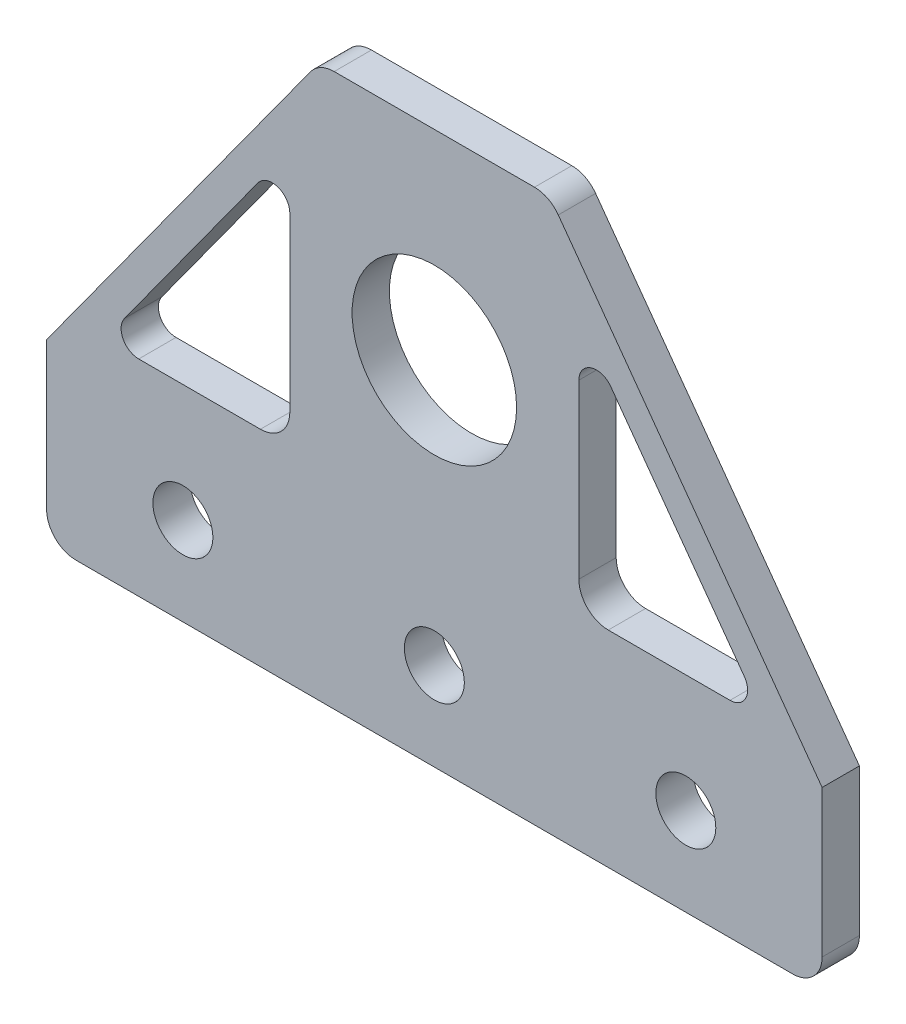
SolidWorks part; units mm, degrees
material "6061-T6 (SS)"
ref_plane "Front Plane" through (0, 0, 0) normal (0, 0, 1) x (1, 0, 0)
ref_plane "Top Plane" through (0, 0, 0) normal (0, 1, 0) x (1, 0, 0)
ref_plane "Right Plane" through (0, 0, 0) normal (1, 0, 0) x (0, 0, -1)
sketch "Sketch1" plane through (0, 0, 0) normal (0, 0, 1) x (1, 0, 0)
  line L0 (9.8, 25) -> (9.8, 52)
  line L1 (-9.8, 25) -> (-9.8, 52)
  line L2 (-9.8, 47) -> (9.8, 47) construction
  line L3 (9.8, 52) -> (-9.8, 52)
  line L4 (9.8, 25) -> (9.8, 10)
  line L5 (-9.8, 25) -> (-9.8, 10)
  line L6 (0, 10) -> (0, 25) construction
  line L12 (9.8, 25) -> (-9.8, 25)
  line L13 (9.8, 10) -> (-9.8, 10)
  line L20 (9.8, 52) -> (9.8, 57)
  line L21 (9.8, 57) -> (-9.8, 57)
  line L22 (-9.8, 57) -> (-9.8, 52)
  circle A2 centre (0, 17.5) radius 2.5527
  circle A3 centre (0, 40) radius 7
  point P15 (0, 47)
  dimension "D3" = 5
  dimension "D4" = 5
  dimension "D5" = 19.6
  dimension "D6" = 15
  dimension "D2" = 15
extrude "Boss-Extrude1" add sketch "Sketch1" along normal blind 3.175
sketch "Sketch2" plane through (0, 0, 3.175) normal (0, 0, 1) x (1, 0, 0)
  line L0 (33, 25) -> (9.8, 25)
  line L4 (-9.8, 57) -> (-9.8, 10)
  line L5 (-9.8, 10) -> (9.8, 10)
  line L6 (9.8, 10) -> (9.8, 57)
  line L7 (9.8, 57) -> (-9.8, 57)
  line L8 (-9.8, 57) -> (-9.8, 10)
  line L9 (-9.8, 10) -> (9.8, 10)
  line L10 (9.8, 10) -> (9.8, 57)
  line L11 (9.8, 57) -> (-9.8, 57)
  line L12 (-33, 25) -> (-33, 10)
  line L13 (-33, 10) -> (33, 10)
  line L14 (33, 10) -> (33, 25)
  line L15 (33, 25) -> (-33, 25)
  line L16 (-33, 25) -> (-33, 10)
  line L17 (-33, 10) -> (33, 10)
  line L18 (33, 10) -> (33, 25)
  line L19 (-9.8, 25) -> (-33, 25)
  circle A0 centre (21.4, 17.5) radius 2.5527 construction
  circle A1 centre (-21.4, 17.5) radius 2.5527 construction
  circle A2 centre (21.4, 17.5) radius 2.5527
  circle A3 centre (-21.4, 17.5) radius 2.5527
  line M12 (9.8, 10) -> (9.8, 57)
  dimension "D1" = 0
  dimension "D2" = 0
extrude "Boss-Extrude2" add sketch "Sketch2" against normal up to surface (3.175 mm away) contours L17 L18 L0 A2 M12 | L8 L19 L16 L17 A3 up to face at (7, 40, 0)
sketch "Sketch3" plane through (0, 0, 0) normal (0, 0, -1) x (-1, 0, 0)
  line L0 (-9.8, 57) -> (-33, 25)
  line L1 (33, 25) -> (9.8, 57)
  line L2 (28.0996, 27.5) -> (12.3, 49.2925)
  line L3 (12.3, 27.5) -> (12.3, 49.2925)
  line L4 (28.0996, 27.5) -> (12.3, 27.5)
  line L5 (-12.3, 49.2925) -> (-28.0996, 27.5)
  line L6 (-12.3, 27.5) -> (-28.0996, 27.5)
  line L7 (-12.3, 49.2925) -> (-12.3, 27.5)
  line L8 (-33, 10) -> (33, 10)
  line L9 (33, 10) -> (33, 25)
  line L10 (33, 25) -> (9.8, 25)
  line L11 (9.8, 25) -> (9.8, 57)
  line L12 (9.8, 57) -> (-9.8, 57)
  line L13 (-9.8, 57) -> (-9.8, 25)
  line L14 (-9.8, 25) -> (-33, 25)
  line L15 (-33, 25) -> (-33, 10)
  line L16 (-33, 10) -> (33, 10)
  line L17 (33, 10) -> (33, 25)
  line L18 (33, 25) -> (9.8, 25)
  line L19 (9.8, 25) -> (9.8, 57)
  line L20 (9.8, 57) -> (-9.8, 57)
  line L21 (-9.8, 57) -> (-9.8, 25)
  line L22 (-9.8, 25) -> (-33, 25)
  line L23 (-33, 25) -> (-33, 10)
  line M17 (33, 25) -> (9.8, 25)
  line M18 (9.8, 25) -> (9.8, 57)
  line M20 (-9.8, 57) -> (-9.8, 25)
  line M21 (-9.8, 25) -> (-33, 25)
  dimension "D1" = 0
  dimension "D2" = 2.5
  dimension "D3" = 2.5
extrude "Boss-Extrude3" add sketch "Sketch3" against normal up to surface (3.175 mm away) contours L1 L2 L4 L3 M17 M18 | L0 L5 L7 L6 M20 M21 up to face at (7, 40, 3.175)
fillet "Fillet1" radius 2.5 2 edges at (12.3, 27.5, 1.5875) (-12.3, 27.5, 1.5875)
fillet "Fillet2" radius 1.5 4 edges at (28.0996, 27.5, 1.5875) (12.3, 49.2925, 1.5875) (-12.3, 49.2925, 1.5875) (-28.0996, 27.5, 1.5875)
fillet "Fillet3" radius 2.5 4 edges at (33, 10, 1.5875) (-33, 10, 1.5875) (9.8, 57, 1.5875) (-9.8, 57, 1.5875)
sketch "Sketch4" plane through (0, 0, 3.175) normal (0, 0, 1) x (1, 0, 0)
  circle A0 centre (0, 40) radius 7 construction
  circle A1 centre (0, 40) radius 7
  circle A2 centre (0, 40) radius 7.8
  dimension "D1" = 15.6
split line "Split Line1" [suppressed]
